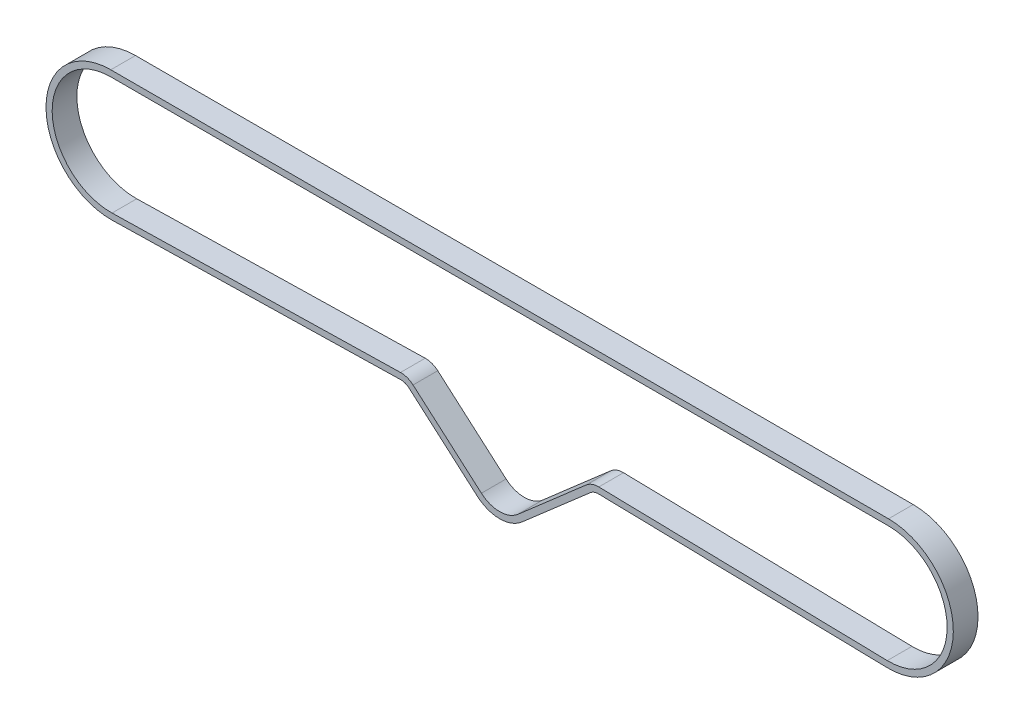
SolidWorks part; units mm, degrees
ref_plane "Alzado" through (0, 0, 0) normal (0, 0, 1) x (1, 0, 0)
ref_plane "Planta" through (0, 0, 0) normal (0, 1, 0) x (1, 0, 0)
ref_plane "Vista lateral" through (0, 0, 0) normal (1, 0, 0) x (0, 0, -1)
sketch "Croquis2" plane through (0, 0, 0) normal (0, 0, 1) x (1, 0, 0)
  line L0 (0, 0) -> (1, 0) construction
  line L1 (0, 0) -> (0, 1) construction
  line L2 (-338.1835, -126.4748) -> (-282.8278, -78.2099)
  line L3 (-276.0427, -75.7495) -> (-42.3761, -80.7359)
  line L4 (-41.256, 24.2521) -> (-671.256, 24.2521)
  line L5 (-670.1359, -80.7359) -> (-436.4694, -75.7495)
  line L6 (-429.6842, -78.2099) -> (-374.3285, -126.4748)
  arc A0 (-374.3285, -126.4748) -> (-338.1835, -126.4748) centre (-356.256, -105.7472) ccw
  arc A1 (-282.8278, -78.2099) -> (-276.0427, -75.7495) centre (-276.256, -85.7472) cw
  arc A2 (-42.3761, -80.7359) -> (-41.256, 24.2521) centre (-41.256, -28.2479) ccw
  arc A3 (-671.256, 24.2521) -> (-670.1359, -80.7359) centre (-671.256, -28.2479) ccw
  arc A4 (-436.4694, -75.7495) -> (-429.6842, -78.2099) centre (-436.256, -85.7472) cw
extrude "Extruir-Lámina1" add sketch "Croquis2" against normal blind 20 thin thin type one direction reverse wall 5
